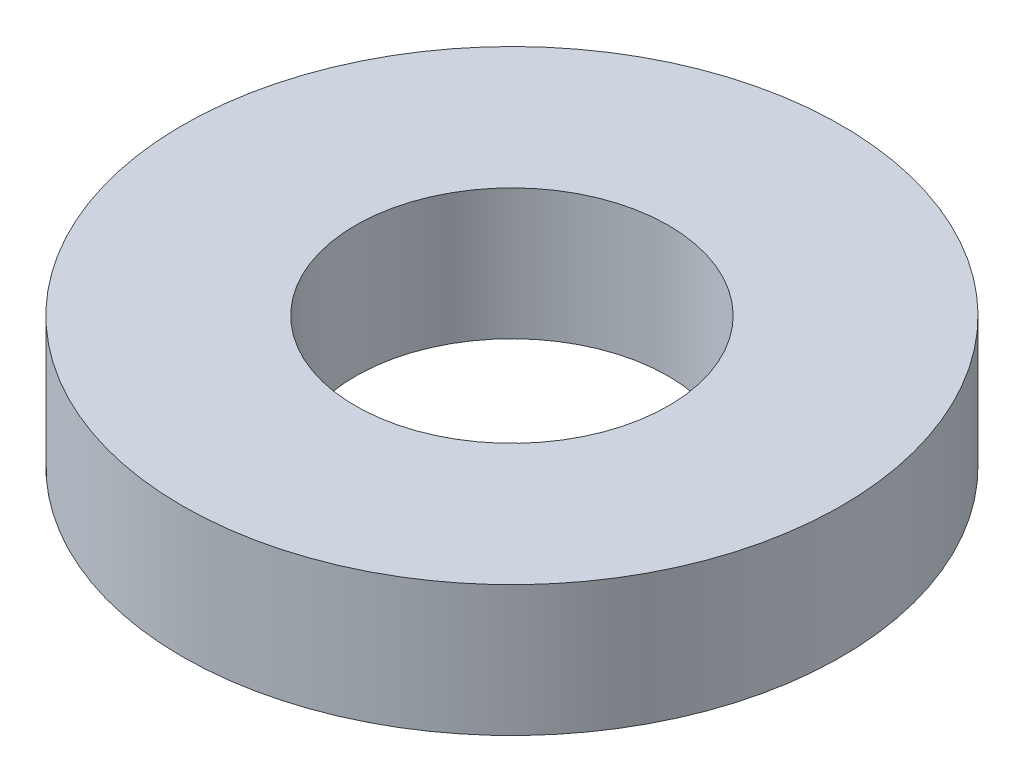
SolidWorks part; units mm, degrees
ref_plane "Front Plane" through (0, 0, 0) normal (0, 0, 1) x (1, 0, 0)
ref_plane "Top Plane" through (0, 0, 0) normal (0, 1, 0) x (1, 0, 0)
ref_plane "Right Plane" through (0, 0, 0) normal (1, 0, 0) x (0, 0, -1)
sketch "Sketch1" plane through (0, 0, 0) normal (0, 1, 0) x (1, 0, 0)
  circle A0 centre (0, 0) radius 12.36
  dimension "D1" = 24.72
extrude "Boss-Extrude1" add sketch "Sketch1" along normal blind 4.9
sketch "Sketch2" plane through (0, 0, 0) normal (0, -1, 0) x (-1, 0, 0)
  circle A0 centre (0, 0) radius 5.8674
  dimension "D1" = 11.7348
extrude "Cut-Extrude1" cut sketch "Sketch2" against normal through all
sketch "Sketch4" plane through (0, 4.9, 0) normal (0, 1, 0) x (1, 0, 0)
  circle A0 centre (0, 0) radius 12.0429 construction
  text T0 "<b>1mm</b>" font "Cambria" height 5.08
extrude "Cut-Extrude2" [suppressed] cut sketch "Sketch4" against normal blind 0.2
